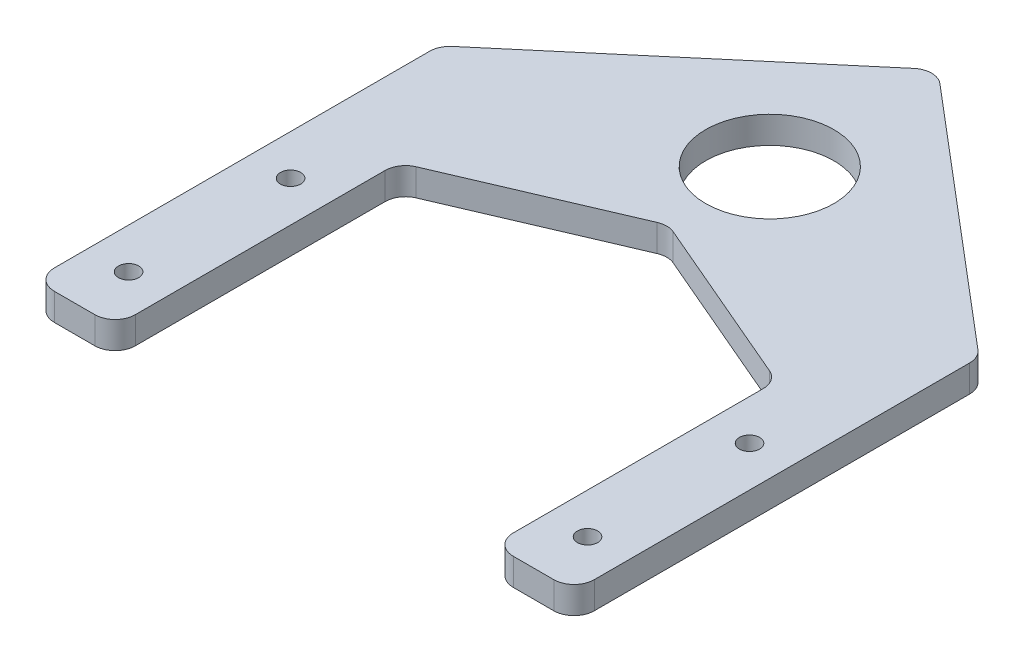
SolidWorks part; units mm, degrees
ref_plane "前视基准面" through (0, 0, 0) normal (0, 0, 1) x (1, 0, 0)
ref_plane "上视基准面" through (0, 0, 0) normal (0, 1, 0) x (1, 0, 0)
ref_plane "右视基准面" through (0, 0, 0) normal (1, 0, 0) x (0, 0, -1)
other "Configuration Table"
sketch "草图2" plane through (0, 0, 0) normal (0, 1, 0) x (1, 0, 0)
  line L0 (0, 0) -> (0, 60)
  line L1 (0, 60) -> (40, 93.9081)
  line L2 (40, 93.9081) -> (80, 60)
  line L3 (80, 60) -> (80, 0)
  line L4 (80, 0) -> (68, 0)
  line L5 (68, 0) -> (68, 42)
  line L6 (68, 42) -> (12, 42) construction
  line L7 (12, 42) -> (12, 0)
  line L8 (12, 0) -> (0, 0)
  line L9 (12, 42) -> (40, 54)
  line L10 (40, 54) -> (68, 42)
  line L11 (40, 93.9081) -> (40, 54) construction
  circle A0 centre (6, 32) radius 1.5
  circle A1 centre (6, 8) radius 1.5
  circle A2 centre (40, 69) radius 9.5
  circle A3 centre (74, 8) radius 1.5
  circle A4 centre (74, 32) radius 1.5
  point P21 (40, 53.1664)
  dimension "D5" = 3
  dimension "D6" = 8
  dimension "D7" = 24
  dimension "D8" = 6
  dimension "D9" = 19
  dimension "D10" = 27
  dimension "D11" = 19
  dimension "D1" = 80
  dimension "D2" = 12
  dimension "D3" = 12
  dimension "D4" = 60
  dimension "D12" = 12
  dimension "D13" = 10
extrude "凸台-拉伸1" add sketch "草图2" along normal blind 4
fillet "圆角1" radius 3 10 edges at (0, 2, 0) (0, 2, -60) (80, 2, -60) (80, 2, 0) (68, 2, 0) (68, 2, -42) (40, 2, -54) (12, 2, -42) (12, 2, 0) (40, 2, -93.9081)
